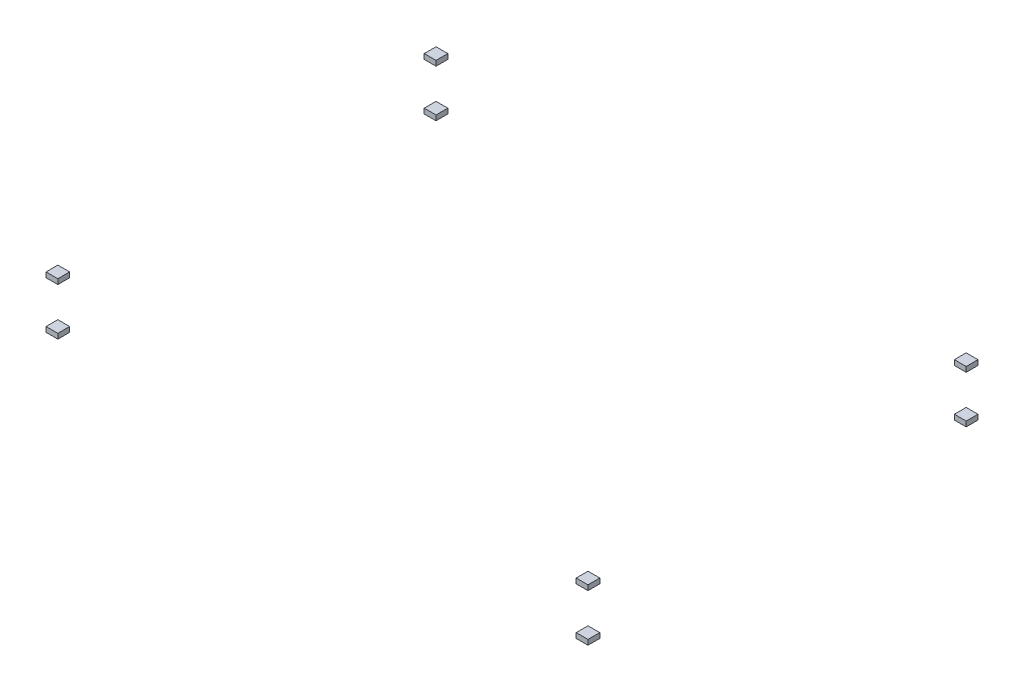
SolidWorks part; units mm, degrees
ref_plane "Front Plane" through (0, 0, 0) normal (0, 0, 1) x (1, 0, 0)
ref_plane "Top Plane" through (0, 0, 0) normal (0, 1, 0) x (1, 0, 0)
ref_plane "Right Plane" through (0, 0, 0) normal (1, 0, 0) x (0, 0, -1)
sketch "Sketch1" plane through (0, 0, 0) normal (0, 0, 1) x (1, 0, 0)
  line L1 (-3210, -310) -> (-3070, -310)
  line L2 (-3210, -310) -> (-3210, -250)
  line L3 (-3210, -250) -> (-3070, -250)
  line L4 (-3070, -310) -> (-3070, -250)
extrude "Boss-Extrude1" add sketch "Sketch1" along normal blind 140 from offset 2310
sketch "Sketch2" plane through (0, 0, 0) normal (0, 0, 1) x (1, 0, 0)
  line L1 (-3210, -310) -> (-3070, -310)
  line L2 (-3210, -310) -> (-3210, -250)
  line L3 (-3210, -250) -> (-3070, -250)
  line L4 (-3070, -310) -> (-3070, -250)
extrude "Boss-Extrude2" add sketch "Sketch2" along normal blind 140 from offset 2170
sketch "Sketch3" plane through (0, 0, 0) normal (0, 0, 1) x (1, 0, 0)
  line L1 (-3210, 250) -> (-3070, 250)
  line L2 (-3210, 250) -> (-3210, 310)
  line L3 (-3210, 310) -> (-3070, 310)
  line L4 (-3070, 250) -> (-3070, 310)
extrude "Boss-Extrude3" add sketch "Sketch3" along normal blind 140 from offset 2310
sketch "Sketch4" plane through (0, 0, 0) normal (0, 0, 1) x (1, 0, 0)
  line L1 (-3210, 250) -> (-3070, 250)
  line L2 (-3210, 250) -> (-3210, 310)
  line L3 (-3210, 310) -> (-3070, 310)
  line L4 (-3070, 250) -> (-3070, 310)
extrude "Boss-Extrude4" add sketch "Sketch4" along normal blind 140 from offset 2170
sketch "Sketch5" plane through (0, 0, 0) normal (0, 0, 1) x (1, 0, 0)
  line L1 (3070, -310) -> (3210, -310)
  line L2 (3070, -310) -> (3070, -250)
  line L3 (3070, -250) -> (3210, -250)
  line L4 (3210, -310) -> (3210, -250)
extrude "Boss-Extrude5" add sketch "Sketch5" along normal blind 140 from offset 2310
sketch "Sketch6" plane through (0, 0, 0) normal (0, 0, 1) x (1, 0, 0)
  line L1 (3070, -310) -> (3210, -310)
  line L2 (3070, -310) -> (3070, -250)
  line L3 (3070, -250) -> (3210, -250)
  line L4 (3210, -310) -> (3210, -250)
extrude "Boss-Extrude6" add sketch "Sketch6" along normal blind 140 from offset 2170
sketch "Sketch7" plane through (0, 0, 0) normal (0, 0, 1) x (1, 0, 0)
  line L1 (3070, 250) -> (3210, 250)
  line L2 (3070, 250) -> (3070, 310)
  line L3 (3070, 310) -> (3210, 310)
  line L4 (3210, 250) -> (3210, 310)
extrude "Boss-Extrude7" add sketch "Sketch7" along normal blind 140 from offset 2310
sketch "Sketch8" plane through (0, 0, 0) normal (0, 0, 1) x (1, 0, 0)
  line L1 (3070, 250) -> (3210, 250)
  line L2 (3070, 250) -> (3070, 310)
  line L3 (3070, 310) -> (3210, 310)
  line L4 (3210, 250) -> (3210, 310)
extrude "Boss-Extrude8" add sketch "Sketch8" along normal blind 140 from offset 2170
